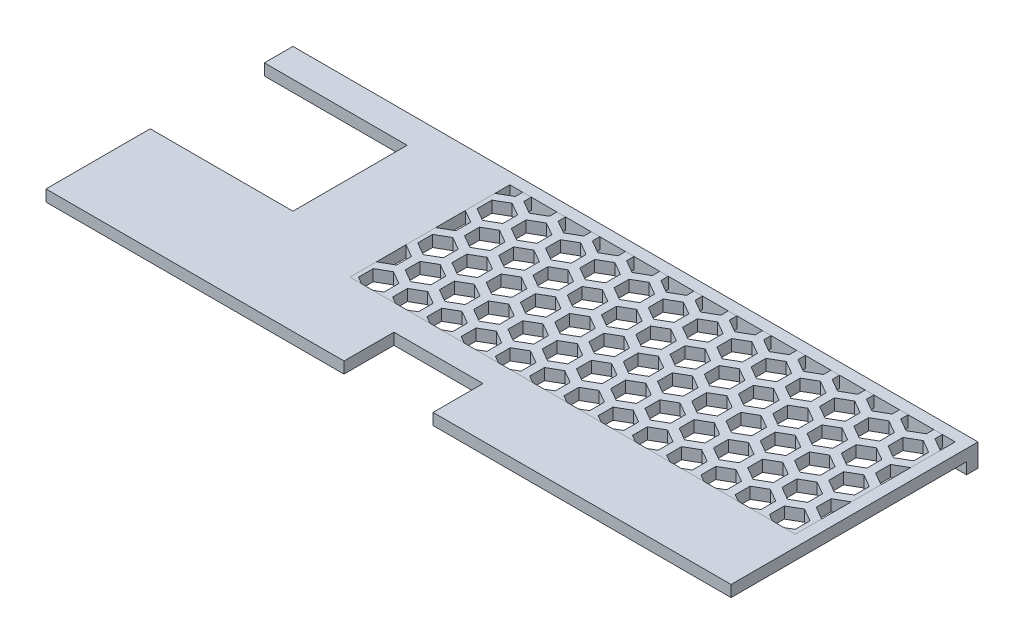
SolidWorks part; units mm, degrees
ref_plane "前视基准面" through (0, 0, 0) normal (0, 0, 1) x (1, 0, 0)
ref_plane "上视基准面" through (0, 0, 0) normal (0, 1, 0) x (1, 0, 0)
ref_plane "右视基准面" through (0, 0, 0) normal (1, 0, 0) x (0, 0, -1)
sketch "草图1" plane through (0, 0, 0) normal (0, 1, 0) x (1, 0, 0)
  line L1 (-87.1566, 32.7606) -> (32.8434, 32.7606)
  line L2 (-87.1566, 32.7606) -> (-87.1566, -12.2394)
  line L3 (-87.1566, -12.2394) -> (32.8434, -12.2394)
  line L4 (32.8434, 32.7606) -> (32.8434, -12.2394)
  line L5 (-34.9566, -1.7394) -> (-19.3566, -1.7394)
  line L6 (-34.9566, -1.7394) -> (-34.9566, -9.7394)
  line L7 (-34.9566, -9.7394) -> (-19.3566, -9.7394)
  line L8 (-19.3566, -1.7394) -> (-19.3566, -9.7394)
  dimension "D1" = 8
  dimension "D2" = 15.6
  dimension "D3" = 52.2
  dimension "D4" = 120
  dimension "D5" = 45
  dimension "D6" = 2.5
extrude "凸台-拉伸1" add sketch "草图1" along normal blind 2
sketch "草图2" plane through (0, 2, 0) normal (0, 1, 0) x (1, 0, 0)
  line L2 (-87.1566, 27.7606) -> (-87.1566, 7.7606)
  line L3 (-87.1566, 7.7606) -> (-62.1566, 7.7606)
  line L4 (-62.1566, 27.7606) -> (-62.1566, 7.7606)
  line L7 (-87.1566, 27.7606) -> (-62.1566, 27.7606)
  line L8 (32.8434, 32.7606) -> (-87.1566, 32.7606) construction
  dimension "D1" = 20
  dimension "D2" = 5
  dimension "D3" = 25
extrude "切除-拉伸1" cut sketch "草图2" against normal blind 2
sketch "草图3" plane through (0, 0, 0) normal (0, -1, 0) x (1, 0, 0)
  line L1 (32.8434, -32.7606) -> (-87.1566, -32.7606)
  line L2 (32.8434, -32.7606) -> (32.8434, -30.7606)
  line L3 (32.8434, -30.7606) -> (-87.1566, -30.7606)
  line L4 (-87.1566, -32.7606) -> (-87.1566, -30.7606)
extrude "凸台-拉伸3" add sketch "草图3" along normal blind 2
sketch "草图4" plane through (0, 0, 12.2394) normal (0, 0, 1) x (1, 0, 0)
  line L1 (32.8434, 2) -> (-87.1566, 2)
  line L2 (32.8434, 2) -> (32.8434, -2)
  line L3 (32.8434, -2) -> (-87.1566, -2)
  line L4 (-87.1566, 2) -> (-87.1566, -2)
extrude "凸台-拉伸4" add sketch "草图4" along normal blind 2
sketch "草图6" plane through (0, 2, 0) normal (0, 1, 0) x (1, 0, 0)
  line L0 (32.8434, 32.7606) -> (-87.1566, 32.7606) construction
  line L1 (-47.1566, 30.7606) -> (30.8434, 30.7606)
  line L2 (-47.1566, 30.7606) -> (-47.1566, 2.7606)
  line L3 (-47.1566, 2.7606) -> (30.8434, 2.7606)
  line L4 (30.8434, 30.7606) -> (30.8434, 2.7606)
  line L5 (32.8434, -14.2394) -> (32.8434, 32.7606) construction
  line L6 (-62.1566, 7.7606) -> (-62.1566, 27.7606) construction
  dimension "D1" = 28
  dimension "D2" = 2
  dimension "D3" = 2
  dimension "D4" = 15
extrude "切除-拉伸2" cut sketch "草图6" against normal blind 2
sketch "草图7" plane through (0, 2, 0) normal (0, 1, 0) x (1, 0, 0)
  line L1 (-47.1566, 30.7606) -> (30.8434, 30.7606)
  line L2 (-47.1566, 30.7606) -> (-47.1566, 2.7606)
  line L3 (-47.1566, 2.7606) -> (30.8434, 2.7606)
  line L4 (30.8434, 30.7606) -> (30.8434, 2.7606)
extrude "凸台-拉伸5" add sketch "草图7" against normal blind 2 separate body
sketch "草图8" plane through (0, 2, 0) normal (0, 1, 0) x (1, 0, 0)
  line L1 (30.8434, 28.1625) -> (33.0934, 29.4615)
  line L2 (33.0934, 29.4615) -> (33.0934, 32.0596)
  line L3 (33.0934, 32.0596) -> (30.8434, 33.3586)
  line L4 (30.8434, 33.3586) -> (28.5934, 32.0596)
  line L5 (28.5934, 32.0596) -> (28.5934, 29.4615)
  line L6 (28.5934, 29.4615) -> (30.8434, 28.1625)
  line L7 (27.8434, 22.9663) -> (30.0934, 24.2654)
  line L8 (30.0934, 24.2654) -> (30.0934, 26.8635)
  line L9 (30.0934, 26.8635) -> (27.8434, 28.1625)
  line L10 (27.8434, 28.1625) -> (25.5934, 26.8635)
  line L11 (25.5934, 26.8635) -> (25.5934, 24.2654)
  line L12 (25.5934, 24.2654) -> (27.8434, 22.9663)
  circle A0 centre (30.8434, 30.7606) radius 2.25 construction
  circle A1 centre (27.8434, 25.5644) radius 2.25 construction
  dimension "D1" = 3
  dimension "D2" = 5.1962
extrude "切除-拉伸3" cut sketch "草图8" against normal blind 2
pattern_linear "阵列(线性)2" count 16 spacing 6 along (-1, 0, 0) count 3 spacing 10.3923 along (0, 0, 1) of "切除-拉伸3"
sketch "草图10" plane through (0, 0, 14.2394) normal (0, 0, 1) x (1, 0, 0)
  line L1 (32.8434, -2) -> (-87.1566, -2)
  line L2 (32.8434, -2) -> (32.8434, 2)
  line L3 (32.8434, 2) -> (-87.1566, 2)
  line L4 (-87.1566, -2) -> (-87.1566, 2)
extrude "切除-拉伸4" cut sketch "草图10" against normal blind 3.75
sketch "草图11" plane through (0, 0, 9.7394) normal (0, 0, -1) x (-1, 0, 0)
  line L1 (34.9566, 2) -> (19.3566, 2)
  line L2 (34.9566, 2) -> (34.9566, 0)
  line L3 (34.9566, 0) -> (19.3566, 0)
  line L4 (19.3566, 2) -> (19.3566, 0)
extrude "切除-拉伸5" cut sketch "草图11" against normal blind 5
